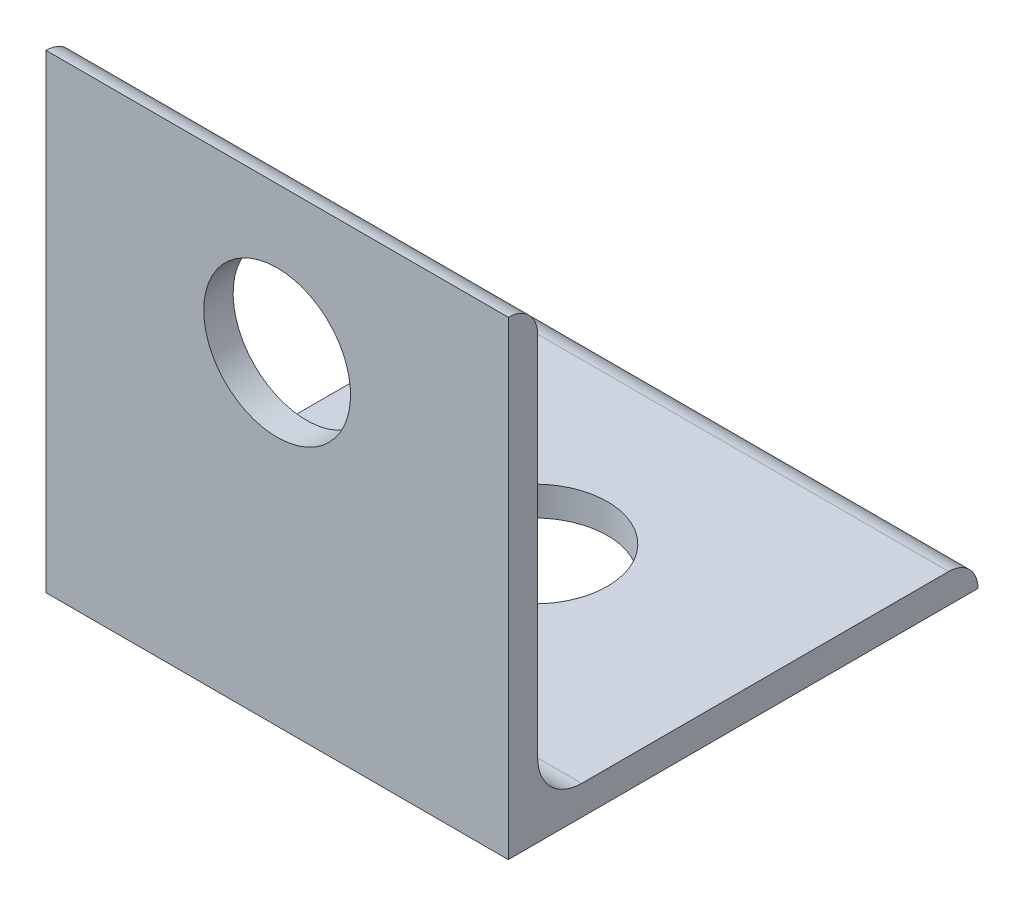
SolidWorks part; units mm, degrees
ref_plane "Alzado" through (0, 0, 0) normal (0, 0, 1) x (1, 0, 0)
ref_plane "Planta" through (0, 0, 0) normal (0, 1, 0) x (1, 0, 0)
ref_plane "Vista lateral" through (0, 0, 0) normal (1, 0, 0) x (0, 0, -1)
sketch "Sketch2" plane through (0, 0, 0) normal (0, 1, 0) x (1, 0, 0)
  line L0 (0, 0) -> (50, 0)
  dimension "D1" = 50
other "Angle iron 2 X 2 X 0.125(1)"
ref_plane "Plane1" through (0, 0, 0) normal (1, 0, 0) x (0, 0, -1)
sketch "Sketch1" plane through (0, 0, 0) normal (1, 0, 0) x (0, 0, -1)
  line L0 (0, 0) -> (0, 50.8)
  line L1 (0, 50.8) -> (0.0051, 50.8)
  line L2 (3.175, 47.6301) -> (3.175, 7.9375)
  line L3 (7.9375, 3.175) -> (47.6301, 3.175)
  line L4 (50.8, 0.0051) -> (50.8, 0)
  line L5 (50.8, 0) -> (0, 0)
  arc A0 (50.8, 0.0051) -> (47.6301, 3.175) centre (47.6301, 0.0051) ccw
  arc A1 (0.0051, 50.8) -> (3.175, 47.6301) centre (0.0051, 47.6301) cw
  arc A2 (7.9375, 3.175) -> (3.175, 7.9375) centre (7.9375, 7.9375) cw
  point P10 (25.4, 0)
  point P14 (0, 25.4)
  point P15 (3.175, 25.4)
  point P16 (25.4, 3.175)
  point P17 (3.175, 50.8)
  point P18 (50.8, 3.175)
  point P19 (0, 0)
  dimension "D2" = 0.0051
  dimension "Radius_1" = 4.7625
  dimension "D1" = 3.175
  dimension "H_leg" = 50.8
sketch "Sketch3" plane through (0, 0, -3.175) normal (0, 0, -1) x (-1, 0, 0)
  line L2 (-25, 7.9375) -> (-25, 47.6301) construction
  line L4 (0, 7.9375) -> (0, 47.6301)
  line L5 (0, 47.6301) -> (-50, 47.6301)
  line L6 (-50, 47.6301) -> (-50, 7.9375)
  line L7 (-50, 7.9375) -> (0, 7.9375)
  line L8 (0, 7.9375) -> (0, 47.6301) construction
  line L9 (0, 47.6301) -> (-50, 47.6301) construction
  line L10 (-50, 47.6301) -> (-50, 7.9375) construction
  line L11 (-50, 7.9375) -> (0, 7.9375) construction
  circle A0 centre (-25, 34.9975) radius 7.9375
  dimension "D2" = 15.875
  dimension "D3" = 27.06
  dimension "D1" = 0
sketch "Sketch4" plane through (0, 3.175, 0) normal (0, 1, 0) x (1, 0, 0)
  line L0 (0, 47.6301) -> (50, 7.9375) construction
  line L1 (0, 7.9375) -> (50, 47.6301) construction
  line L2 (25, 7.9375) -> (25, 47.6301) construction
  line L4 (0, 47.6301) -> (0, 7.9375)
  line L5 (0, 7.9375) -> (50, 7.9375)
  line L6 (50, 7.9375) -> (50, 47.6301)
  line L7 (50, 47.6301) -> (0, 47.6301)
  line L8 (0, 47.6301) -> (0, 7.9375) construction
  line L9 (0, 7.9375) -> (50, 7.9375) construction
  line L10 (50, 7.9375) -> (50, 47.6301) construction
  line L11 (50, 47.6301) -> (0, 47.6301) construction
  circle A0 centre (25, 27.7838) radius 7.9375
  dimension "D2" = 15.875
  dimension "D1" = 0
extrude "Cut-Extrude1" cut sketch "Sketch4" against normal up to surface (3.175 mm away) up to face at (25, 0, -25.4)
extrude "Cut-Extrude2" cut sketch "Sketch3" against normal up to surface (3.175 mm away) contours A0 up to face at (25, 25.4, 0)
sketch "Sketch5" plane through (0, 0, 0) normal (0, -1, 0) x (1, 0, 0)
  line L4 (0, 0) -> (0, -50.8)
  line L5 (0, -50.8) -> (50, -50.8)
  line L6 (50, -50.8) -> (50, 0)
  line L7 (50, 0) -> (0, 0)
  line L8 (0, 0) -> (0, -50.8)
  line L9 (0, -50.8) -> (50, -50.8)
  line L10 (50, -50.8) -> (50, 0)
  line L11 (50, 0) -> (0, 0)
  circle A0 centre (25, -27.7838) radius 7.9375 construction
  circle A1 centre (25, -27.7838) radius 7.9375
  dimension "D1" = 0
